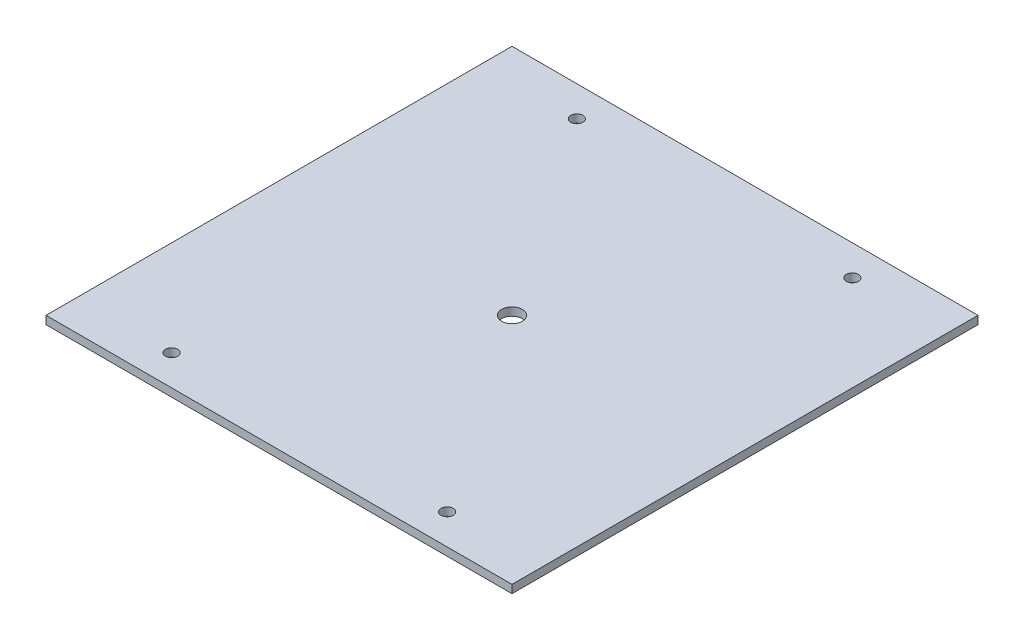
SolidWorks part; units mm, degrees
ref_plane "Front Plane" through (0, 0, 0) normal (0, 0, 1) x (1, 0, 0)
ref_plane "Top Plane" through (0, 0, 0) normal (0, 1, 0) x (1, 0, 0)
ref_plane "Right Plane" through (0, 0, 0) normal (1, 0, 0) x (0, 0, -1)
sketch "Sketch1" plane through (0, 0, 0) normal (0, 1, 0) x (1, 0, 0)
  line L1 (-57.5, 57.5) -> (57.5, 57.5)
  line L2 (-57.5, 57.5) -> (-57.5, -57.5)
  line L3 (-57.5, -57.5) -> (57.5, -57.5)
  line L4 (57.5, 57.5) -> (57.5, -57.5)
  line L5 (-57.5, 57.5) -> (57.5, -57.5) construction
  line L6 (-57.5, -57.5) -> (57.5, 57.5) construction
  circle A0 centre (0, 0) radius 2.55
  point P0 (0, 0)
  dimension "D2" = 5.1
  dimension "D1" = 115
extrude "Boss-Extrude1" add sketch "Sketch1" along normal blind 2
hole_wizard "Ø3.0mm Dowel Hole1" positions "Sketch2" profile "Sketch3" hole size "Ø3.0" standard "ANSI Metric" end condition through all
sketch "Sketch2" plane through (0, 2, 0) normal (0, 1, 0) x (1, 0, 0)
  line L8 (-34, 50) -> (34, 50)
  line L9 (-34, 50) -> (-34, -50)
  line L10 (-34, -50) -> (34, -50)
  line L11 (34, 50) -> (34, -50)
  line L12 (-34, 50) -> (34, -50) construction
  line L13 (-34, -50) -> (34, 50) construction
  point P95 (34, 50)
  point P98 (34, -50)
  point P101 (-34, -50)
  point P104 (-34, 50)
  point P107 (0, 0)
  dimension "D1" = 34
  dimension "D2" = 50
sketch "Sketch3" plane through (-34, 2, -50) normal (1, 0, 0) x (0, 0, 1)
  line L0 (0, 0) -> (0, 2)
  line L1 (0, 2) -> (1.5, 2)
  line L2 (1.5, 2) -> (1.5, 0)
  line L5 (1.5, 0) -> (0, 0)
  line L11 (0, -6.35) -> (0, 107.95) construction
  dimension "Thru Hole Dia." = 3
  dimension "Thru Hole Depth" = 2
